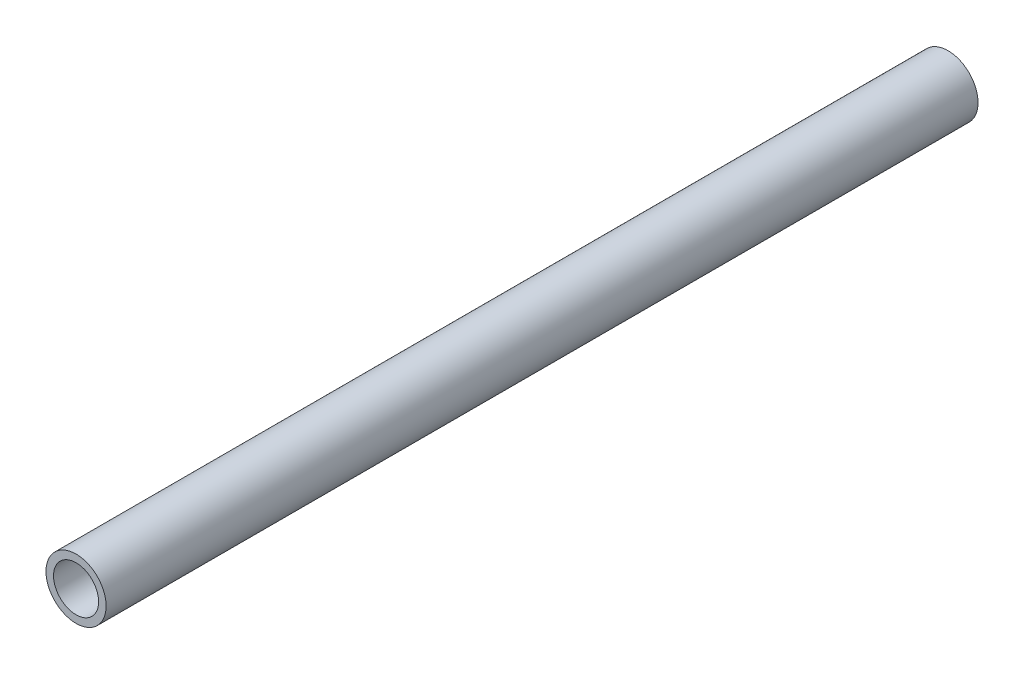
SolidWorks part; units mm, degrees
ref_plane "前视基准面" through (0, 0, 0) normal (0, 0, 1) x (1, 0, 0)
ref_plane "上视基准面" through (0, 0, 0) normal (0, 1, 0) x (1, 0, 0)
ref_plane "右视基准面" through (0, 0, 0) normal (1, 0, 0) x (0, 0, -1)
sketch "草图1" plane through (0, 0, 0) normal (0, 0, 1) x (1, 0, 0)
  circle A0 centre (0, 0) radius 2
  circle A1 centre (0, 0) radius 1.5
  dimension "D1" = 4
  dimension "D2" = 3
extrude "凸台-拉伸1" add sketch "草图1" along normal mid plane 58
